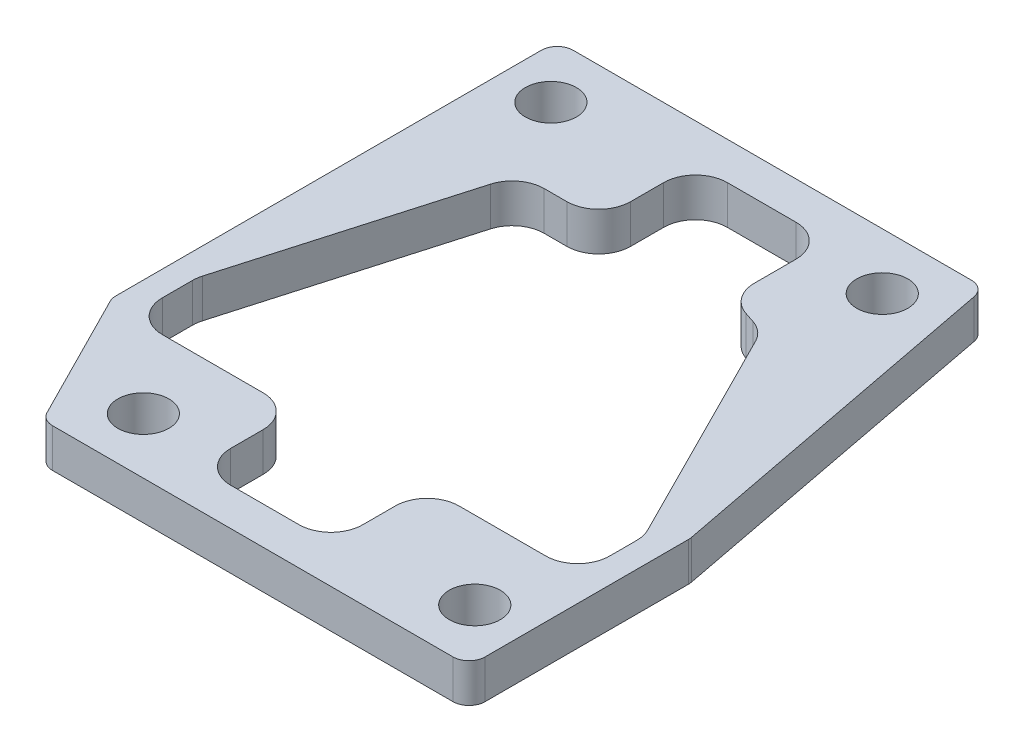
SolidWorks part; units mm, degrees
ref_plane "Front Plane" through (0, 0, 0) normal (0, 0, 1) x (1, 0, 0)
ref_plane "Top Plane" through (0, 0, 0) normal (0, 1, 0) x (1, 0, 0)
ref_plane "Right Plane" through (0, 0, 0) normal (1, 0, 0) x (0, 0, -1)
sketch "Sketch1" plane through (0, 0, 0) normal (0, 1, 0) x (1, 0, 0)
  line L0 (-2.6924, 4.4704) -> (28.984, 4.4704)
  line L1 (30.2313, 3.4397) -> (35.5724, -24.3971)
  line L2 (35.5952, -24.6364) -> (35.5952, -40.8357)
  line L3 (34.3252, -42.1057) -> (2.4658, -42.1057)
  line L4 (1.3329, -41.4097) -> (-3.8253, -31.2286)
  line L5 (-3.9624, -30.6546) -> (-3.9624, 3.2004)
  line L6 (26.3652, 0) -> (30.7306, 0.8376) construction
  line L7 (5.2422, -37.6607) -> (0.6199, -40.0025) construction
  line L8 (12.5603, 1.4859) -> (18.0213, 1.4859)
  line L9 (20.5613, -1.0541) -> (20.5613, -4.3746)
  line L10 (22.3043, -6.7863) -> (23.1387, -7.062)
  line L11 (24.61, -8.3307) -> (33.3295, -25.634)
  line L12 (33.6013, -26.777) -> (33.6013, -28.9231)
  line L13 (24.1652, -31.4631) -> (31.0613, -31.4631)
  line L14 (21.6252, -34.0031) -> (21.6252, -36.5812)
  line L15 (19.0852, -39.1212) -> (13.6496, -39.1212)
  line L16 (11.1096, -36.5812) -> (11.1096, -34.0031)
  line L17 (8.5696, -31.4631) -> (0.5588, -31.4631)
  line L18 (-1.9812, -28.9231) -> (-1.9812, -26.5317)
  line L19 (-1.882, -25.8287) -> (3.2389, -8.0474)
  line L20 (5.6797, -6.2103) -> (7.4803, -6.2103)
  line L21 (10.0203, -3.6703) -> (10.0203, -1.0541)
  circle A0 centre (0, 0) radius 2.032
  circle A1 centre (26.3652, 0) radius 2.032
  circle A2 centre (5.2422, -37.6607) radius 2.032
  circle A3 centre (31.6074, -37.6607) radius 2.032
  arc A4 (-1.882, -25.8287) -> (-1.9812, -26.5317) centre (0.5588, -26.5317) ccw
  arc A5 (-1.9812, -28.9231) -> (0.5588, -31.4631) centre (0.5588, -28.9231) ccw
  arc A6 (11.1096, -34.0031) -> (8.5696, -31.4631) centre (8.5696, -34.0031) ccw
  arc A7 (11.1096, -36.5812) -> (13.6496, -39.1212) centre (13.6496, -36.5812) ccw
  arc A8 (19.0852, -39.1212) -> (21.6252, -36.5812) centre (19.0852, -36.5812) ccw
  arc A9 (33.6013, -28.9231) -> (31.0613, -31.4631) centre (31.0613, -28.9231) cw
  arc A10 (24.1652, -31.4631) -> (21.6252, -34.0031) centre (24.1652, -34.0031) ccw
  arc A11 (33.6013, -26.777) -> (33.3295, -25.634) centre (31.0613, -26.777) ccw
  arc A12 (24.61, -8.3307) -> (23.1387, -7.062) centre (22.3417, -9.4738) ccw
  arc A13 (22.3043, -6.7863) -> (20.5613, -4.3746) centre (23.1013, -4.3746) cw
  arc A14 (20.5613, -1.0541) -> (18.0213, 1.4859) centre (18.0213, -1.0541) ccw
  arc A15 (12.5603, 1.4859) -> (10.0203, -1.0541) centre (12.5603, -1.0541) ccw
  arc A16 (10.0203, -3.6703) -> (7.4803, -6.2103) centre (7.4803, -3.6703) cw
  arc A17 (5.6797, -6.2103) -> (3.2389, -8.0474) centre (5.6797, -8.7503) ccw
  arc A18 (34.3252, -42.1057) -> (35.5952, -40.8357) centre (34.3252, -40.8357) ccw
  arc A19 (35.5952, -24.6364) -> (35.5724, -24.3971) centre (34.3252, -24.6364) ccw
  arc A20 (30.2313, 3.4397) -> (28.984, 4.4704) centre (28.984, 3.2004) ccw
  arc A21 (-2.6924, 4.4704) -> (-3.9624, 3.2004) centre (-2.6924, 3.2004) ccw
  arc A22 (-3.9624, -30.6546) -> (-3.8253, -31.2286) centre (-2.6924, -30.6546) ccw
  arc A23 (1.3329, -41.4097) -> (2.4658, -42.1057) centre (2.4658, -40.8357) ccw
  point P26 (-1.9812, -26.1732)
  point P38 (11.1096, -31.4631)
  point P45 (33.6013, -31.4631)
  point P48 (21.6252, -31.4631)
  point P51 (33.6013, -26.1732)
  point P54 (24.1369, -7.3919)
  point P57 (20.5613, -6.2103)
  point P64 (10.0203, -6.2103)
  point P67 (3.768, -6.2103)
  point P72 (35.5952, -24.5157)
  point P75 (30.0335, 4.4704)
  point P80 (-3.9624, -30.958)
  point P83 (1.6855, -42.1057)
  dimension "D1" = 4.064
  dimension "D2" = 26.3652
  dimension "D3" = 26.3652
  dimension "D4" = 43.18
  dimension "D5" = 38.0238
  dimension "D6" = 3.9624
  dimension "D8" = 4.4704
  dimension "D28" = 2.54
  dimension "D29" = 1.27
  dimension "D7" = 4.445
  dimension "D9" = 29.5148
  dimension "D10" = 3.9878
  dimension "D11" = 4.445
  dimension "D12" = 5.1816
  dimension "D13" = 12.4968
  dimension "D14" = 2.9845
  dimension "D15" = 1.9939
  dimension "D16" = 2.9845
  dimension "D17" = 1.9812
  dimension "D18" = 10.541
  dimension "D19" = 13.9827
  dimension "D20" = 10.6807
  dimension "D21" = 13.97
  dimension "D22" = 10.5156
  dimension "D23" = 10.6426
  dimension "D24" = 5.2899
  dimension "D25" = 20.7743
  dimension "D26" = 21.0312
  dimension "D27" = 3.5756
extrude "Boss-Extrude1" add sketch "Sketch1" along normal blind 3.0861
